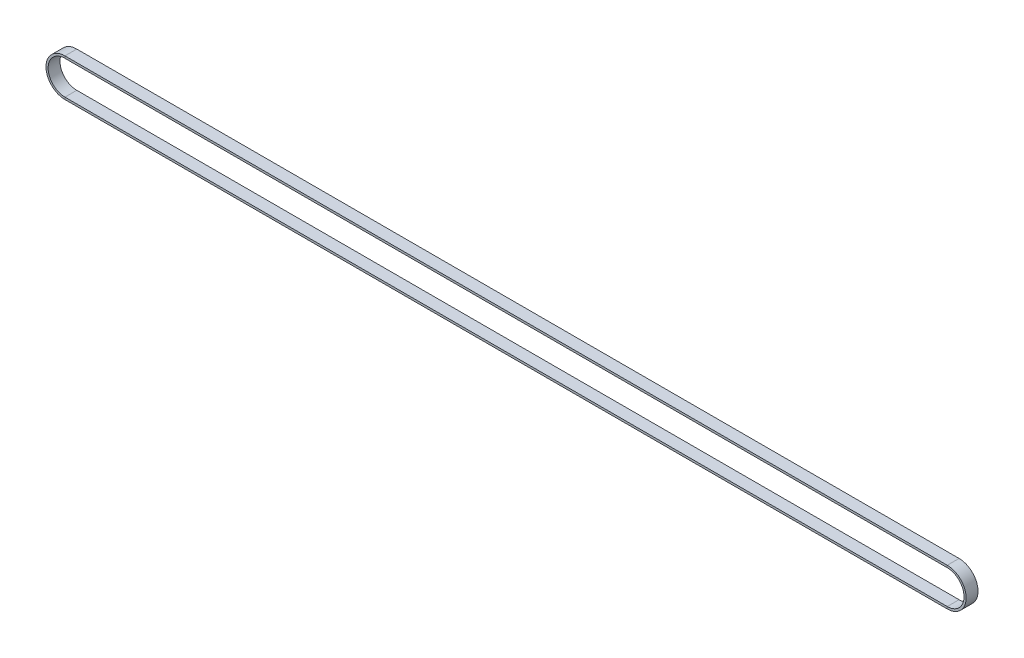
SolidWorks part; units mm, degrees
ref_plane "Front Plane" through (0, 0, 0) normal (0, 0, 1) x (1, 0, 0)
ref_plane "Top Plane" through (0, 0, 0) normal (0, 1, 0) x (1, 0, 0)
ref_plane "Right Plane" through (0, 0, 0) normal (1, 0, 0) x (0, 0, -1)
sketch "Sketch2" plane through (0, 0, 0) normal (0, 0, 1) x (1, 0, 0)
  line L0 (0, 0) -> (1, 0) construction
  line L1 (0, 0) -> (0, 1) construction
  line L2 (4.7625, 3.8013) -> (478.3039, 3.8013)
  line L3 (478.3039, -16.5187) -> (4.7625, -16.5187)
  arc A0 (4.7625, -16.5187) -> (4.7625, 3.8013) centre (4.7625, -6.3587) cw
  arc A1 (478.3039, 3.8013) -> (478.3039, -16.5187) centre (478.3039, -6.3587) cw
ref_plane "Plane1" through (0, 0, 0) normal (0, 0, 1) x (1, 0, 0)
ref_plane "Plane2" through (4.7625, 3.8013, 0) normal (1, 0, 0) x (0, 0, -1)
sketch "Sketch3" plane through (4.7625, 3.8013, 0) normal (1, 0, 0) x (0, 0, -1)
  line L0 (0, 0) -> (0, -1.143) construction
  line L1 (0, 0) -> (0, -20.32) construction
  line L2 (0, 0) -> (0, -20.32) construction
  line L3 (-3.175, -1.143) -> (3.175, -1.143)
  line L4 (3.175, -1.143) -> (3.175, 0)
  line L5 (3.175, 0) -> (-3.175, 0)
  line L6 (-3.175, -1.143) -> (-3.175, 0)
  point P10 (3.175, -0.9996)
  point P11 (0, 0)
  dimension "D1" = 6.35
  dimension "D2" = 1.143
sweep "Sweep1" add profiles "Sketch3" path "Sketch2"
